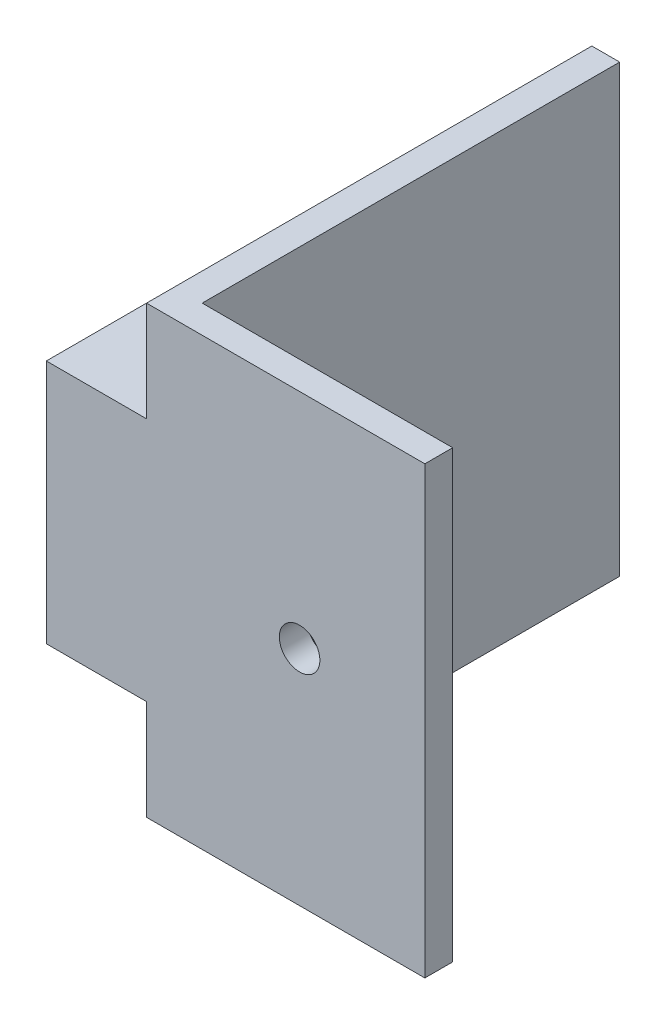
SolidWorks part; units mm, degrees
ref_plane "Front Plane" through (0, 0, 0) normal (0, 0, 1) x (1, 0, 0)
ref_plane "Top Plane" through (0, 0, 0) normal (0, 1, 0) x (1, 0, 0)
ref_plane "Right Plane" through (0, 0, 0) normal (1, 0, 0) x (0, 0, -1)
sketch "Sketch2" plane through (0, 0, 0) normal (0, 1, 0) x (1, 0, 0)
  line L0 (0, 0) -> (0, 50.8)
  line L1 (0, 50.8) -> (3.175, 50.8)
  line L2 (3.175, 50.8) -> (3.175, 3.175)
  line L3 (3.175, 3.175) -> (31.75, 3.175)
  line L4 (31.75, 3.175) -> (31.75, 0)
  line L5 (31.75, 0) -> (0, 0)
  dimension "D1" = 3.175
  dimension "D2" = 3.175
  dimension "D3" = 31.75
  dimension "D4" = 50.8
extrude "Boss-Extrude1" add sketch "Sketch2" along normal blind 50.8
hole_wizard "#12-28 Tapped Hole1" positions "Sketch4" profile "Sketch5" tap size "#12-28" standard "Ansi Inch" end condition through all
sketch "Sketch4" plane through (0, 0, -3.175) normal (0, 0, -1) x (-1, 0, 0)
  line L0 (-17.4625, 0) -> (-17.4625, 50.8) construction
  line L1 (-31.75, 0) -> (-3.175, 0) construction
  line L2 (-31.75, 50.8) -> (-3.175, 50.8) construction
  point P0 (-17.4625, 25.4)
sketch "Sketch5" plane through (17.4625, 25.4, -3.175) normal (1, 0, 0) x (0, 1, 0)
  line L0 (0, 0) -> (0, 3.175)
  line L1 (0, 3.175) -> (2.3114, 3.175)
  line L2 (2.3114, 3.175) -> (2.3114, 0)
  line L5 (2.3114, 0) -> (0, 0)
  line L11 (0, -6.35) -> (0, 107.95) construction
  dimension "Thru Tap Drill Dia." = 4.6228
  dimension "Thru Tap Drill Depth" = 3.175
cosmetic thread "Hole Thread1" parameters "D2"=5.4864
sketch "Sketch6" plane through (0, 0, 0) normal (-1, 0, 0) x (0, 0, 1)
  line L0 (-50.8, 25.4) -> (0, 25.4) construction
  line L1 (-50.8, 50.8) -> (-50.8, 0) construction
  line L2 (0, 50.8) -> (0, 0) construction
  line L4 (-50.8, 11.43) -> (0, 11.43)
  line L5 (-50.8, 11.43) -> (-50.8, 39.37)
  line L6 (-50.8, 39.37) -> (0, 39.37)
  line L7 (0, 11.43) -> (0, 39.37)
  line L8 (-50.8, 11.43) -> (0, 39.37) construction
  line L9 (-50.8, 39.37) -> (0, 11.43) construction
  point P6 (-25.4, 25.4)
  dimension "D1" = 27.94
extrude "Boss-Extrude2" add sketch "Sketch6" along normal blind 11.43
